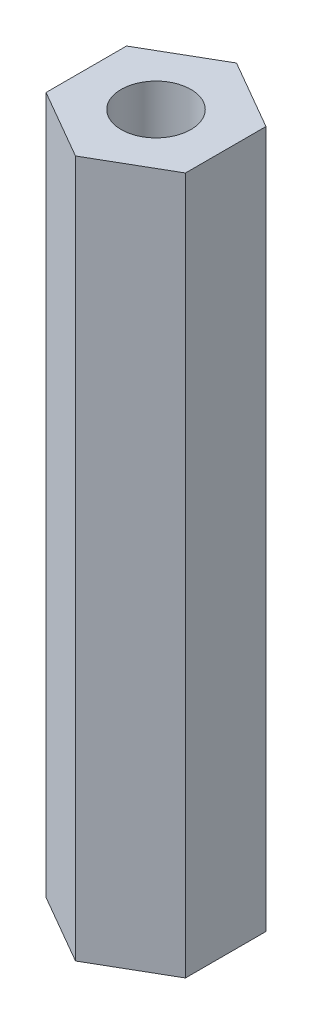
SolidWorks part; units mm, degrees
ref_plane "정면" through (0, 0, 0) normal (0, 0, 1) x (1, 0, 0)
ref_plane "윗면" through (0, 0, 0) normal (0, 1, 0) x (1, 0, 0)
ref_plane "우측면" through (0, 0, 0) normal (1, 0, 0) x (0, 0, -1)
sketch "스케치1" plane through (0, 0, 0) normal (0, 1, 0) x (1, 0, 0)
  line L1 (0, 3.4641) -> (-3, 1.7321)
  line L2 (-3, 1.7321) -> (-3, -1.7321)
  line L3 (-3, -1.7321) -> (0, -3.4641)
  line L4 (0, -3.4641) -> (3, -1.7321)
  line L5 (3, -1.7321) -> (3, 1.7321)
  line L6 (3, 1.7321) -> (0, 3.4641)
  circle A0 centre (0, 0) radius 3 construction
  dimension "D1" = 6
extrude "보스-돌출1" add sketch "스케치1" along normal blind 30
sketch "스케치2" plane through (0, 30, 0) normal (0, 1, 0) x (1, 0, 0)
  circle A0 centre (0, 0) radius 1.5
  dimension "D1" = 3
extrude "컷-돌출1" cut sketch "스케치2" against normal blind 50
